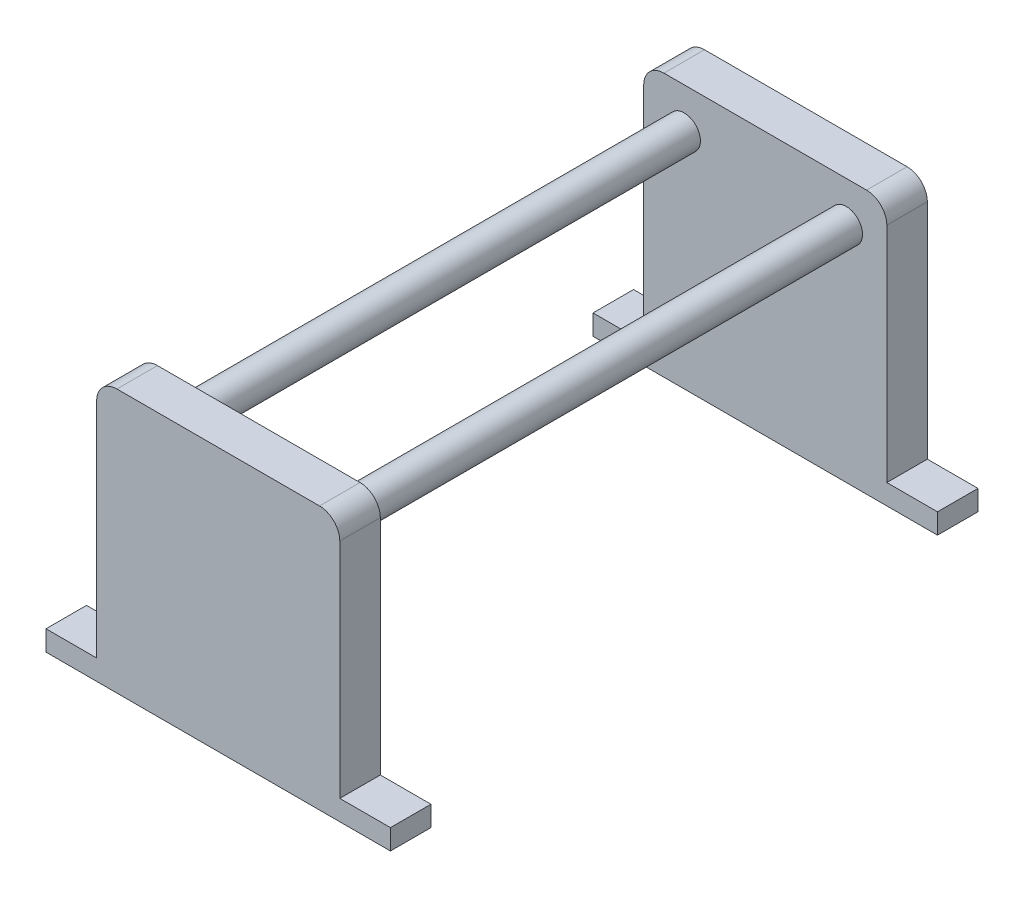
SolidWorks part; units mm, degrees
ref_plane "Alzado" through (0, 0, 0) normal (0, 0, 1) x (1, 0, 0)
ref_plane "Planta" through (0, 0, 0) normal (0, 1, 0) x (1, 0, 0)
ref_plane "Vista lateral" through (0, 0, 0) normal (1, 0, 0) x (0, 0, -1)
sketch "Croquis1" plane through (0, 0, 0) normal (0, 0, 1) x (1, 0, 0)
  line L1 (30, 30) -> (-30, 30)
  line L2 (30, 30) -> (30, -30)
  line L3 (30, -30) -> (-30, -30)
  line L4 (-30, 30) -> (-30, -30)
  line L5 (30, 30) -> (-30, -30) construction
  line L6 (30, -30) -> (-30, 30) construction
  line L7 (-42.5, -30) -> (42.5, -30)
  line L8 (-42.5, -30) -> (-42.5, -35)
  line L9 (-42.5, -35) -> (42.5, -35)
  line L10 (42.5, -30) -> (42.5, -35)
  line L11 (-42.5, -30) -> (42.5, -35) construction
  line L12 (-42.5, -35) -> (42.5, -30) construction
  point P0 (0, 0)
  point P10 (0, -32.5)
  dimension "D1" = 60
  dimension "D2" = 5
  dimension "D3" = 85
extrude "Saliente-Extruir1" add sketch "Croquis1" along normal blind 10 contours L1 L4 L3 L2 | L10 L7 L3 L8 L9
fillet "Redondeo1" radius 5 2 edges at (30, 30, 5) (-30, 30, 5)
sketch "Croquis2" plane through (0, 0, 0) normal (0, 0, -1) x (-1, 0, 0)
  line L0 (0, 30) -> (0, -35) construction
  line L1 (-25, 30) -> (25, 30) construction
  line L2 (42.5, -35) -> (-42.5, -35) construction
  line L3 (-30, 25) -> (-30, -30) construction
  circle A0 centre (-20, 20) radius 4
  circle A1 centre (20, 20) radius 4
  dimension "D1" = 10
  dimension "D3" = 8
  dimension "D2" = 10
extrude "Saliente-Extruir2" add sketch "Croquis2" along normal blind 125
sketch "Croquis3" plane through (0, 0, -125) normal (0, 0, -1) x (-1, 0, 0)
  line L1 (-30, 30) -> (30, 30)
  line L2 (-30, 30) -> (-30, -30)
  line L3 (-30, -30) -> (30, -30)
  line L4 (30, 30) -> (30, -30)
  line L5 (-30, 30) -> (30, -30) construction
  line L6 (-30, -30) -> (30, 30) construction
  line L7 (42.5, -30) -> (-42.5, -30)
  line L8 (42.5, -30) -> (42.5, -35)
  line L9 (42.5, -35) -> (-42.5, -35)
  line L10 (-42.5, -30) -> (-42.5, -35)
  line L11 (42.5, -30) -> (-42.5, -35) construction
  line L12 (42.5, -35) -> (-42.5, -30) construction
  point P4 (0, 0)
  point P10 (0, -32.5)
  circle M2 centre (20, 20) radius 4
  dimension "D1" = 60
extrude "Saliente-Extruir4" add sketch "Croquis3" along normal blind 10 contours L4 L1 L2 L3 M2 | L7 L10 L9 L8 L3 | M2
fillet "Redondeo2" radius 5 2 edges at (30, 30, -130) (-30, 30, -130)
